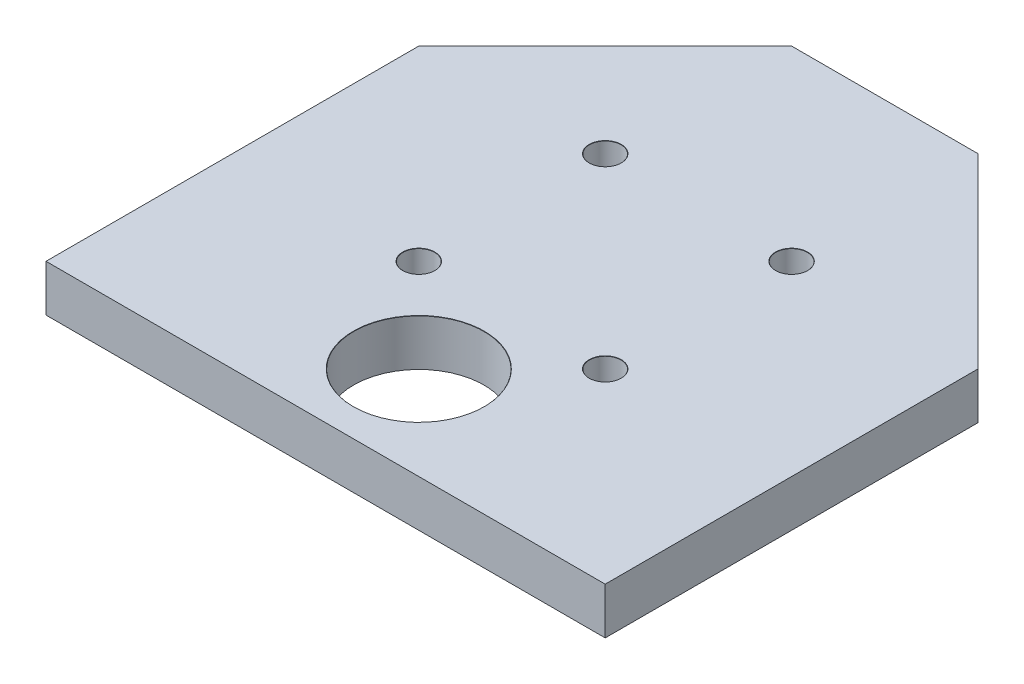
SolidWorks part; units mm, degrees
ref_plane "前视基准面" through (0, 0, 0) normal (0, 0, 1) x (1, 0, 0)
ref_plane "上视基准面" through (0, 0, 0) normal (0, 1, 0) x (1, 0, 0)
ref_plane "右视基准面" through (0, 0, 0) normal (1, 0, 0) x (0, 0, -1)
other "Configuration Table"
sketch "草图1" plane through (0, 0, 0) normal (0, 1, 0) x (1, 0, 0)
  line L0 (-10, 30) -> (-30, 10)
  line L1 (-30, -30) -> (30, -30)
  line L2 (-30, -30) -> (-30, 10)
  line L3 (-10, 30) -> (10, 30)
  line L4 (30, -30) -> (30, 10)
  line L7 (10, 30) -> (30, 10)
  point P0 (0, 0)
  point P3 (0, 30)
  dimension "D1" = 60
  dimension "D2" = 60
  dimension "D3" = 45
  dimension "D4" = 20
  dimension "D5" = 30
extrude "凸台-拉伸1" add sketch "草图1" along normal blind 5
sketch "草图6" plane through (-20, 0, -20) normal (-0.7071, 0, -0.7071) x (-0.7071, 0, 0.7071)
  line L2 (-14.1421, 5) -> (-14.1421, 0) construction
  point P0 (-6.1421, 2.5)
  point P7 (-14.1421, 2.5)
  dimension "D1" = 8
hole_wizard "M3 螺纹孔的螺纹孔钻头1" positions "3D草图1" profile "草图8" hole size "M3" standard "GB"
sketch3d "3D草图1"
  point P0 (-15.6569, 2.5, -24.3431)
sketch "草图8" plane through (-15.6569, 2.5, -24.3431) normal (0, 1, 0) x (-0.7071, 0, 0.7071)
  line L0 (0, 0) -> (0, 10.7511)
  line L1 (0, 10.7511) -> (1.25, 10)
  line L2 (1.25, 10) -> (1.25, 0.025)
  line L3 (1.25, 0.025) -> (1.275, 0)
  line L5 (1.275, 0) -> (0, 0)
  line L6 (-1.25, 0.025) -> (-1.275, 0) construction
  line L10 (0, 10.7511) -> (-1.25, 10) construction
  line L11 (0, -6.35) -> (0, 107.95) construction
  dimension "孔直径" = 2.5
  dimension "孔深度" = 10
  dimension "近端锥形沉头孔直径" = 2.55
  dimension "近端锥形沉头孔角度" = 90
  dimension "导头角度" = 118
sketch "草图9" plane through (0, 5, 0) normal (0, 1, 0) x (1, 0, 0)
  point P0 (0, -20)
  dimension "D1" = 20
hole_wizard "M16 螺纹孔的螺纹孔钻头1" positions "3D草图2" profile "草图10" hole size "M16" standard "GB" end condition through all
sketch3d "3D草图2"
  point P0 (0, 5, 20)
sketch "草图10" plane through (0, 5, 20) normal (1, 0, 0) x (0, 0, 1)
  line L0 (0, 0) -> (0, 5)
  line L1 (0, 5) -> (7, 5)
  line L2 (7, 5) -> (7, 0.025)
  line L3 (7, 0.025) -> (7.025, 0)
  line L5 (7.025, 0) -> (0, 0)
  line L6 (-7, 0.025) -> (-7.025, 0) construction
  line L11 (0, -6.35) -> (0, 107.95) construction
  dimension "通孔孔直径" = 14
  dimension "通孔孔深度" = 5
  dimension "近端锥形沉头孔直径" = 14.05
  dimension "近端锥形沉头孔角度" = 90
cosmetic thread "装饰螺纹线1" parameters "D2"=15
mirror "镜向2" about plane through (0, 0, 0) normal (1, 0, 0) of "M3 螺纹孔的螺纹孔钻头1"
cosmetic thread "装饰螺纹线2" parameters "D2"=3.5
sketch "草图11" plane through (0, 5, 0) normal (0, 1, 0) x (1, 0, 0)
  line L1 (-10, 10) -> (10, 10)
  line L2 (-10, 10) -> (-10, -10)
  line L3 (-10, -10) -> (10, -10)
  line L4 (10, 10) -> (10, -10)
  line L5 (-10, 10) -> (10, -10) construction
  line L6 (-10, -10) -> (10, 10) construction
  point P0 (0, 0)
  dimension "D1" = 20
  dimension "D2" = 20
hole_wizard "M3 间隙孔1" positions "3D草图3" profile "草图12" hole size "M3" standard "GB" end condition through all
sketch3d "3D草图3"
  point P0 (-10, 5, -10)
  point P3 (10, 5, -10)
  point P6 (10, 5, 10)
  point P9 (-10, 5, 10)
sketch "草图12" plane through (-10, 5, -10) normal (1, 0, 0) x (0, 0, 1)
  line L0 (0, 0) -> (0, 5)
  line L1 (0, 5) -> (1.7, 5)
  line L2 (1.7, 5) -> (1.7, 0.025)
  line L3 (1.7, 0.025) -> (1.725, 0)
  line L5 (1.725, 0) -> (0, 0)
  line L6 (-1.7, 0.025) -> (-1.725, 0) construction
  line L11 (0, -6.35) -> (0, 107.95) construction
  dimension "通孔孔直径" = 3.4
  dimension "通孔孔深度" = 5
  dimension "近端锥形沉头孔直径" = 3.45
  dimension "近端锥形沉头孔角度" = 90
